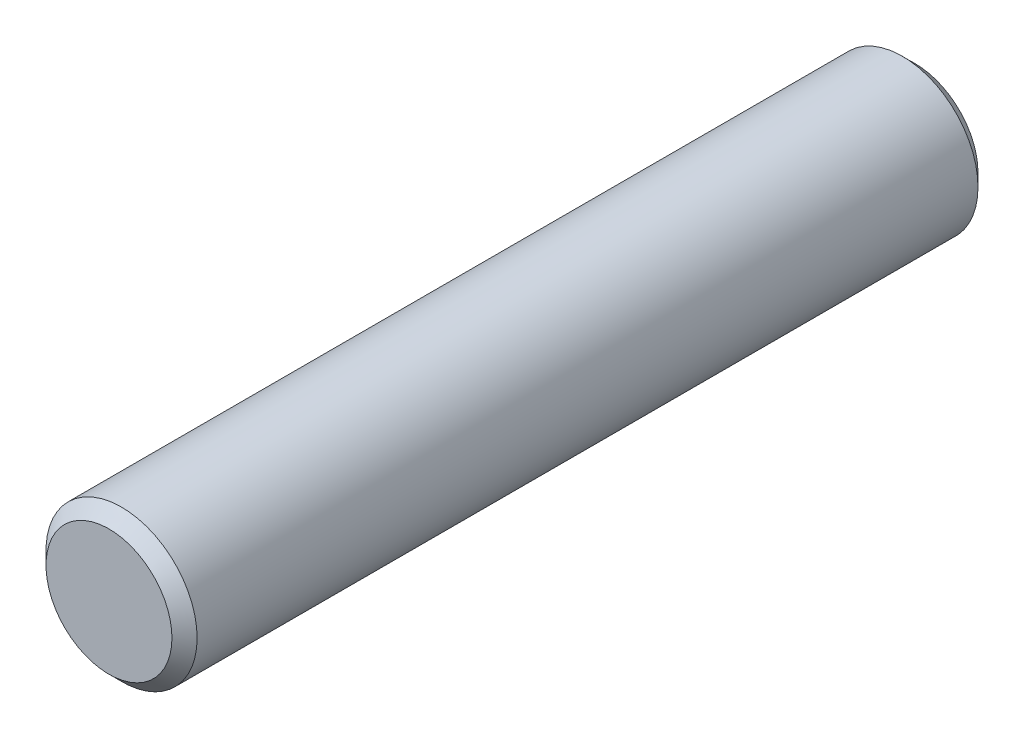
SolidWorks part; units mm, degrees
ref_plane "Front Plane" through (0, 0, 0) normal (0, 0, 1) x (1, 0, 0)
ref_plane "Top Plane" through (0, 0, 0) normal (0, 1, 0) x (1, 0, 0)
ref_plane "Right Plane" through (0, 0, 0) normal (1, 0, 0) x (0, 0, -1)
sketch "Sketch1" plane through (0, 0, 0) normal (0, 0, 1) x (1, 0, 0)
  circle A0 centre (0, 0) radius 3
  dimension "D1" = 6
extrude "Boss-Extrude1" add sketch "Sketch1" along normal mid plane 32
chamfer "Chamfer1" distance 0.5 angle 45 2 edges at (3, 0, -16) (3, 0, 16)
